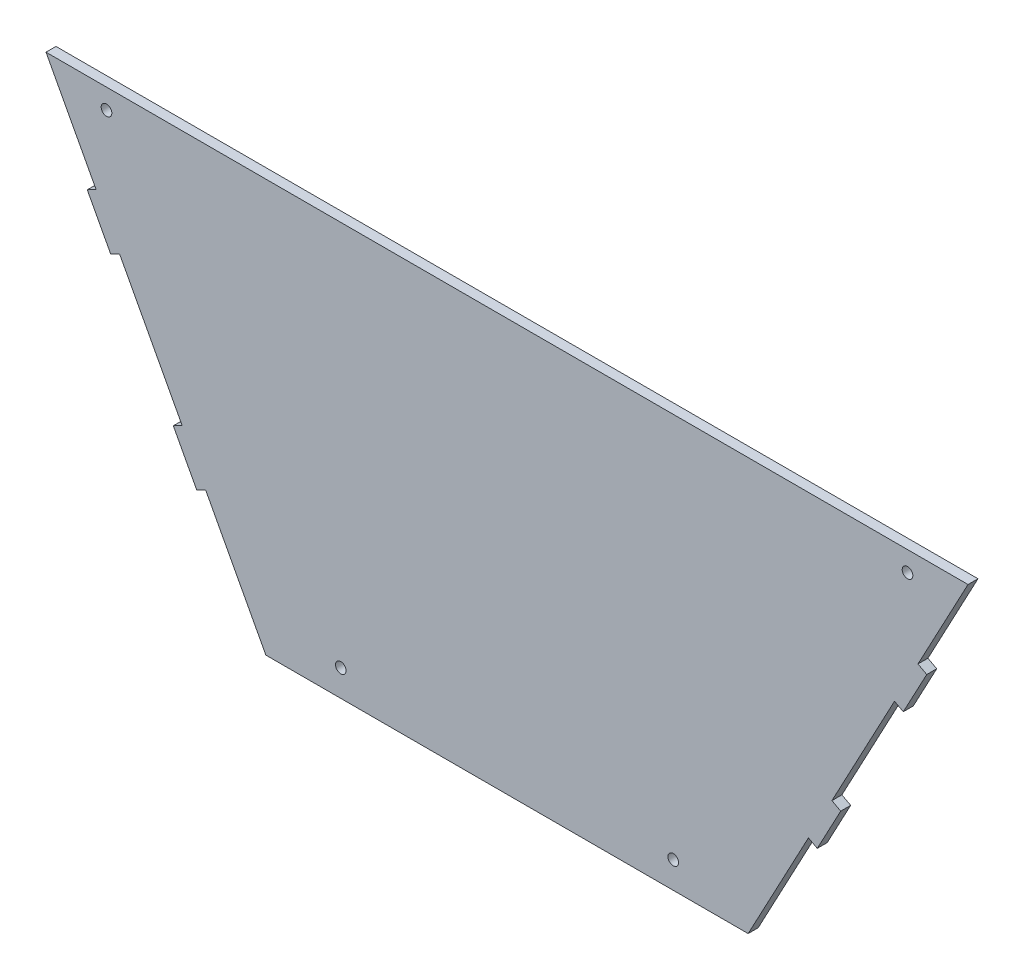
SolidWorks part; units mm, degrees
ref_plane "前视基准面" through (0, 0, 0) normal (0, 0, 1) x (1, 0, 0)
ref_plane "上视基准面" through (0, 0, 0) normal (0, 1, 0) x (1, 0, 0)
ref_plane "右视基准面" through (0, 0, 0) normal (1, 0, 0) x (0, 0, -1)
sketch "草图1" plane through (0, 0, 0) normal (0, 0, 1) x (1, 0, 0)
  line L0 (-138.6667, 62) -> (-72.5333, -62) construction
  line L1 (-72.5333, -62) -> (72.5333, -62) construction
  line L2 (72.5333, -62) -> (138.6667, 62) construction
  line L3 (-72, -63) -> (72, -63) construction
  line L4 (-80, -48) -> (80, -48) construction
  line L5 (-138.6667, 62) -> (138.6667, 62) construction
  line L6 (0, 62) -> (0, -62) construction
  line L7 (-138.6667, 62) -> (138.6667, 62)
  line L8 (138.6667, 62) -> (72.5333, -62)
  line L9 (72.5333, -62) -> (-72.5333, -62)
  line L10 (-72.5333, -62) -> (-138.6667, 62)
  line L11 (-50, -54) -> (50, -54) construction
  line L12 (-120.4667, 56) -> (-135.4667, 56) construction
  line L13 (120.4667, 56) -> (135.4667, 56) construction
  circle A0 centre (-50, -54) radius 1.6
  circle A1 centre (50, -54) radius 1.6
  circle A2 centre (-120.4667, 56) radius 1.6
  circle A3 centre (120.4667, 56) radius 1.6
  point P10 (0, 0)
  point P11 (0, 62)
  point P20 (0, -54)
  dimension "D6" = 3.2
  dimension "D9" = 3.2
  dimension "D1" = 160
  dimension "D2" = 144
  dimension "D3" = 15
  dimension "D4" = 14
  dimension "D5" = 110
  dimension "D7" = 6
  dimension "D8" = 100
  dimension "D10" = 6
  dimension "D11" = 15
extrude "凸台-拉伸1" add sketch "草图1" along normal blind 3
sketch "草图2" plane through (-82.2145, -43.8478, 0) normal (-0.8824, -0.4706, 0) x (0, 0, 1)
  line L0 (0, 119.9608) -> (0, -20.5725) construction
  line L1 (0, 87.9608) -> (3, 87.9608)
  line L2 (0, 87.9608) -> (0, 72.9608)
  line L3 (0, 72.9608) -> (3, 72.9608)
  line L4 (3, 87.9608) -> (3, 72.9608)
  line L5 (3, 119.9608) -> (3, -20.5725) construction
  line L7 (0, 32.9608) -> (3, 32.9608)
  line L8 (0, 32.9608) -> (0, 17.9608)
  line L9 (0, 17.9608) -> (3, 17.9608)
  line L10 (3, 32.9608) -> (3, 17.9608)
  point P14 (1.5, 32.9608)
  dimension "D1" = 32
  dimension "D2" = 15
  dimension "D3" = 15
  dimension "D4" = 40
extrude "凸台-拉伸2" add sketch "草图2" along normal blind 3
mirror "镜向1" about plane through (0, 0, 0) normal (1, 0, 0) of "凸台-拉伸2"
